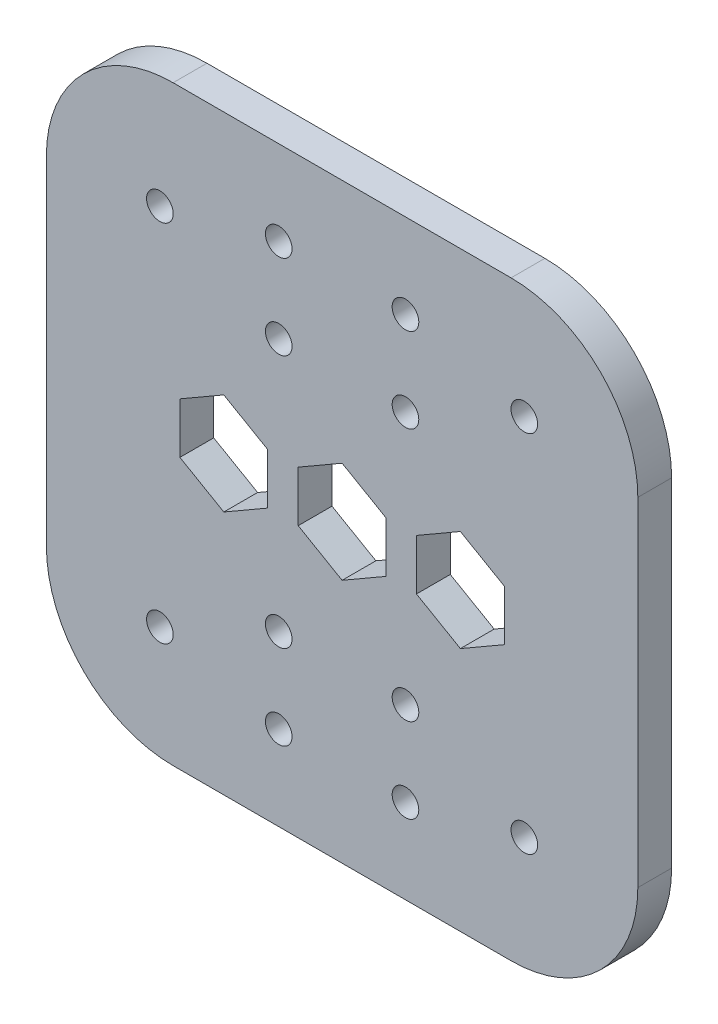
SolidWorks part; units mm, degrees
ref_plane "前视基准面" through (0, 0, 0) normal (0, 0, 1) x (1, 0, 0)
ref_plane "上视基准面" through (0, 0, 0) normal (0, 1, 0) x (1, 0, 0)
ref_plane "右视基准面" through (0, 0, 0) normal (1, 0, 0) x (0, 0, -1)
other "Configuration Table"
sketch "草图1" plane through (0, 0, 0) normal (0, 0, 1) x (1, 0, 0)
  line L1 (0, 0) -> (70, 0)
  line L2 (0, 0) -> (0, -70)
  line L3 (0, -70) -> (70, -70)
  line L4 (70, 0) -> (70, -70)
  dimension "D1" = 70
  dimension "D2" = 70
extrude "凸台-拉伸1" add sketch "草图1" along normal blind 4
sketch "草图2" plane through (0, 0, 4) normal (0, 0, 1) x (1, 0, 0)
  line L0 (35, 0) -> (35, -70) construction
  line L1 (70, 0) -> (0, 0) construction
  line L2 (0, -70) -> (70, -70) construction
  line L3 (0, -15) -> (70, -15) construction
  line L4 (0, 0) -> (0, -70) construction
  line L5 (70, -70) -> (70, 0) construction
  line L6 (0, -35) -> (70, -35) construction
  line L7 (35, -35) -> (13.4332, -13.4332) construction
  line L8 (21, -29) -> (15.8038, -32)
  line L9 (35, -41) -> (40.1962, -38)
  line L10 (40.1962, -38) -> (40.1962, -32)
  line L11 (40.1962, -32) -> (35, -29)
  line L12 (35, -29) -> (29.8038, -32)
  line L13 (29.8038, -32) -> (29.8038, -38)
  line L14 (29.8038, -38) -> (35, -41)
  line L15 (15.8038, -32) -> (15.8038, -38)
  line L16 (15.8038, -38) -> (21, -41)
  line L17 (21, -41) -> (26.1962, -38)
  line L18 (26.1962, -32) -> (21, -29)
  line L19 (26.1962, -38) -> (26.1962, -32)
  line L20 (43.8038, -38) -> (43.8038, -32)
  line L21 (43.8038, -32) -> (49, -29)
  line L22 (49, -41) -> (43.8038, -38)
  line L23 (54.1962, -38) -> (49, -41)
  line L24 (54.1962, -32) -> (54.1962, -38)
  line L25 (49, -29) -> (54.1962, -32)
  circle A0 centre (27.5, -10) radius 1.575
  circle A1 centre (42.5, -10) radius 1.575
  circle A2 centre (42.5, -20) radius 1.575
  circle A3 centre (27.5, -20) radius 1.575
  circle A4 centre (27.5, -50) radius 1.575
  circle A5 centre (42.5, -50) radius 1.575
  circle A6 centre (42.5, -60) radius 1.575
  circle A7 centre (27.5, -60) radius 1.575
  circle A8 centre (13.4332, -13.4332) radius 1.575
  circle A9 centre (56.5668, -13.4332) radius 1.575
  circle A10 centre (56.5668, -56.5668) radius 1.575
  circle A11 centre (13.4332, -56.5668) radius 1.575
  circle A12 centre (35, -35) radius 5.1962 construction
  point P42 (35, -35)
  dimension "D4" = 3.15
  dimension "D6" = 3.15
  dimension "D1" = 20
  dimension "D2" = 7.5
  dimension "D3" = 5
  dimension "D5" = 30.5
  dimension "D7" = 45
  dimension "D9" = 6
  dimension "D11" = 3.6077
  dimension "D10" = 2
  dimension "D8" = 4
extrude "切除-拉伸1" cut sketch "草图2" against normal through all
fillet "圆角1" radius 15 4 edges at (0, -70, 2) (70, -70, 2) (70, 0, 2) (0, 0, 2)
